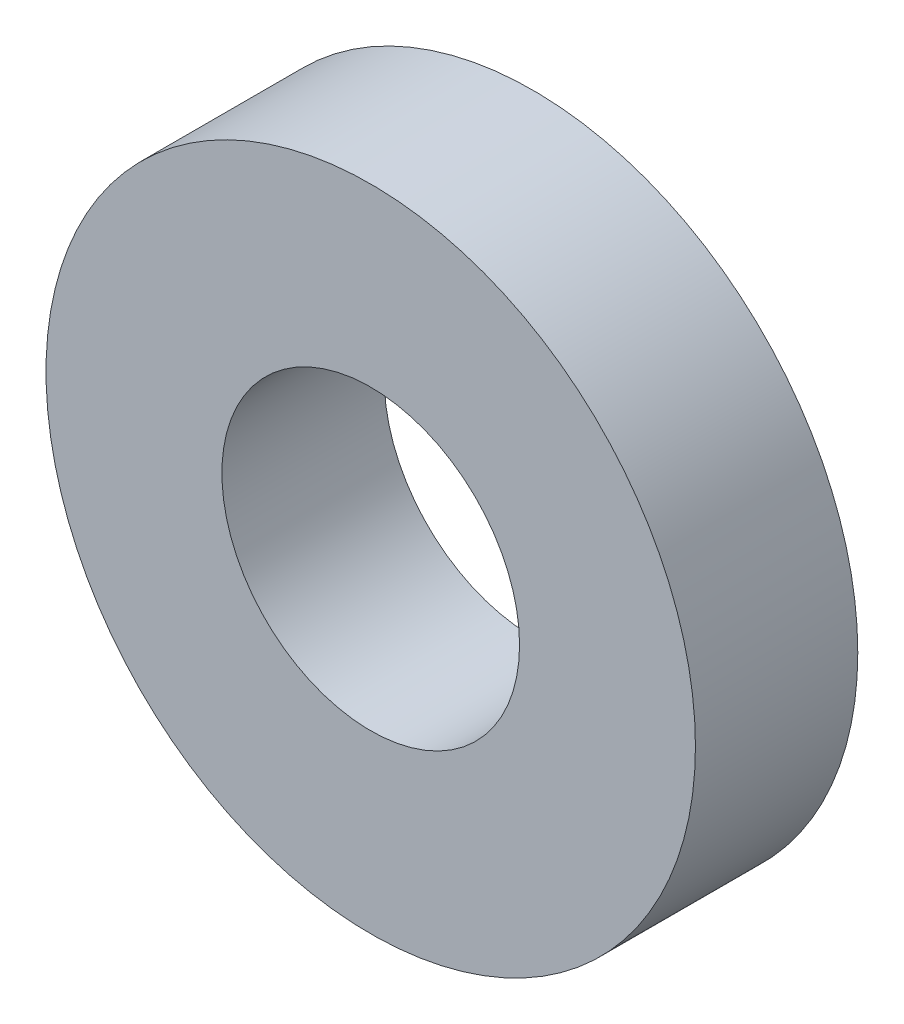
SolidWorks part; units mm, degrees
ref_plane "前视基准面" through (0, 0, 0) normal (0, 0, 1) x (1, 0, 0)
ref_plane "上视基准面" through (0, 0, 0) normal (0, 1, 0) x (1, 0, 0)
ref_plane "右视基准面" through (0, 0, 0) normal (1, 0, 0) x (0, 0, -1)
other "Configuration Table"
sketch "草图1" plane through (0, 0, 0) normal (0, 0, 1) x (1, 0, 0)
  circle A0 centre (0, 0) radius 24
  dimension "diameter" = 48
extrude "Lifting_eye_envelope" add sketch "草图1" along normal blind 12
sketch "草图2" plane through (0, 0, 12) normal (0, 0, 1) x (1, 0, 0)
  circle A0 centre (0, 0) radius 11
  dimension "diameter" = 22
extrude "Shackle_pin_clearance" cut sketch "草图2" against normal through all
